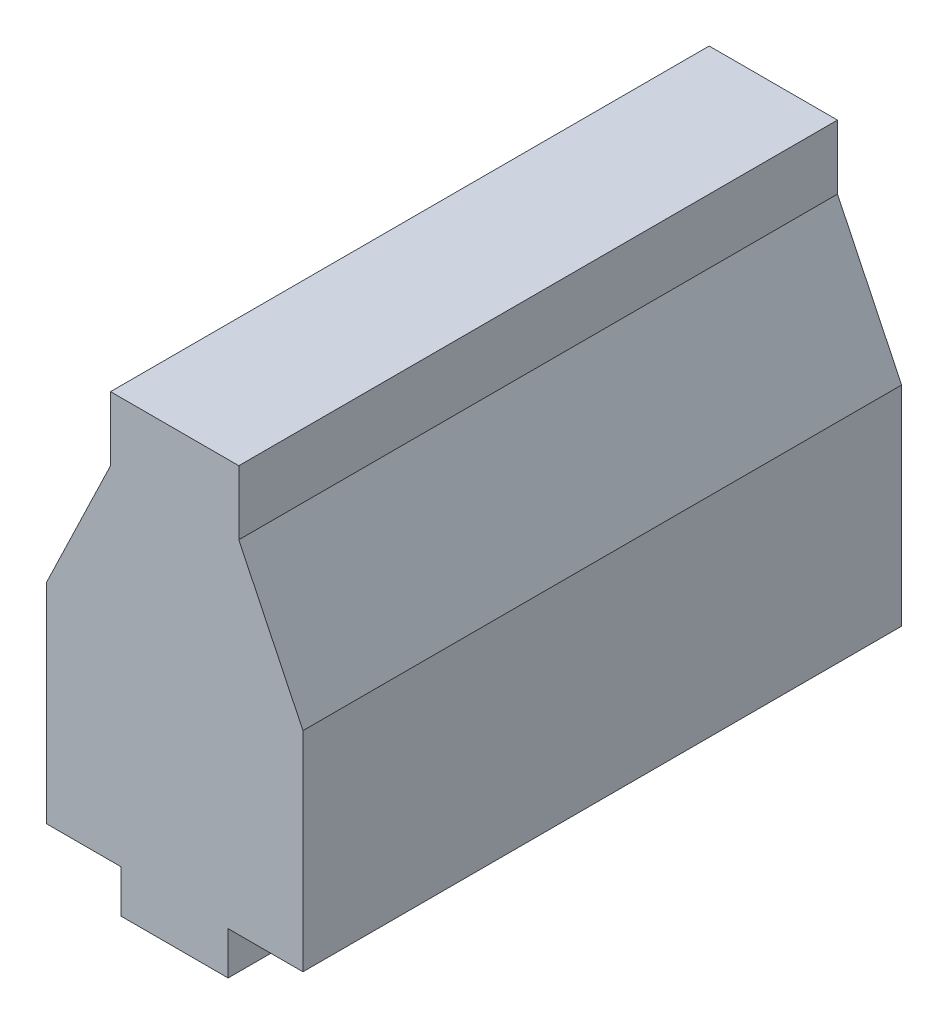
SolidWorks part; units mm, degrees
ref_plane "Front Plane" through (0, 0, 0) normal (0, 0, 1) x (1, 0, 0)
ref_plane "Top Plane" through (0, 0, 0) normal (0, 1, 0) x (1, 0, 0)
ref_plane "Right Plane" through (0, 0, 0) normal (1, 0, 0) x (0, 0, -1)
sketch "Sketch1" plane through (0, 0, 0) normal (0, 0, 1) x (1, 0, 0)
  line L0 (-3, 8.2696) -> (3, 8.2696)
  line L1 (3, 8.2696) -> (3, 5.2696)
  line L3 (-3, 5.2696) -> (-3, 8.2696)
  line L4 (-3, 5.2696) -> (-6, -0.9652)
  line L5 (-6, -0.9652) -> (-6, -10.7304)
  line L6 (-6, -10.7304) -> (-2.5, -10.7304)
  line L7 (6, -10.7304) -> (6, -0.9604)
  line L8 (6, -0.9604) -> (3, 5.2696)
  line L9 (-2.5, -10.7304) -> (-2.5, -12.7304)
  line L10 (-2.5, -12.7304) -> (2.5, -12.7304)
  line L11 (2.5, -12.7304) -> (2.5, -10.7304)
  line L12 (2.5, -10.7304) -> (6, -10.7304)
  dimension "D1" = 6
  dimension "D2" = 3
  dimension "D3" = 3
  dimension "D4" = 16
  dimension "D5" = 12
  dimension "D6" = 6
  dimension "D7" = 9.77
  dimension "D8" = 2
  dimension "D9" = 5
  dimension "D10" = 2.5
extrude "Boss-Extrude1" add sketch "Sketch1" along normal blind 28
